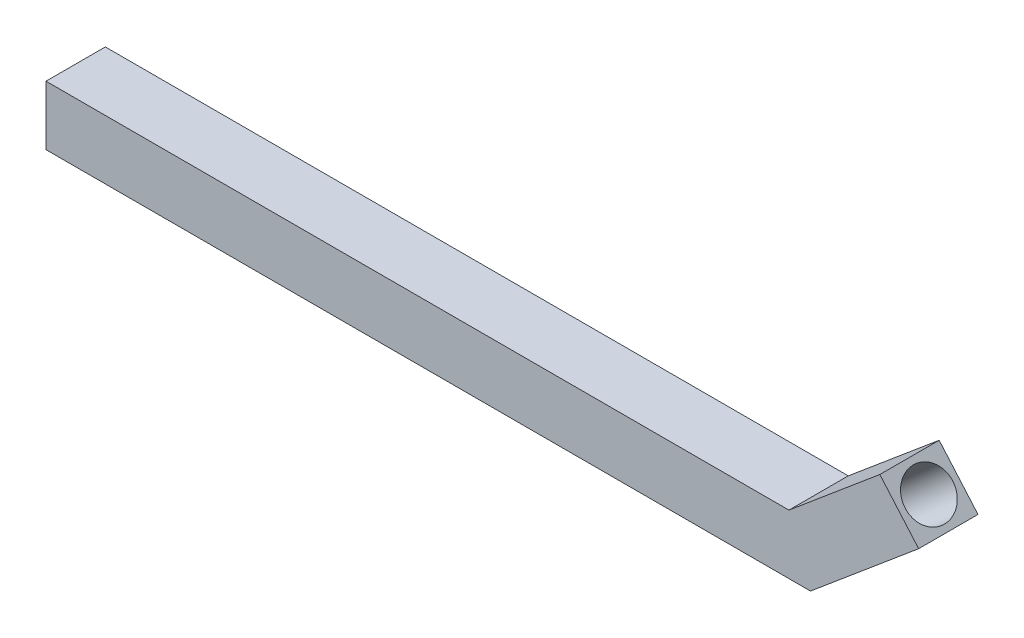
SolidWorks part; units mm, degrees
ref_plane "Front Plane" through (0, 0, 0) normal (0, 0, 1) x (1, 0, 0)
ref_plane "Top Plane" through (0, 0, 0) normal (0, 1, 0) x (1, 0, 0)
ref_plane "Right Plane" through (0, 0, 0) normal (1, 0, 0) x (0, 0, -1)
sketch "Sketch1" plane through (0, 0, 0) normal (0, 0, 1) x (1, 0, 0)
  line L0 (-13.3, 0) -> (0, 0)
  line L1 (0, 0) -> (3.8302, 3.2139)
  line L2 (-13.3, 0) -> (-13.3, -2.5)
  line L3 (-13.3, -2.5) -> (0.9095, -2.5)
  line L4 (0.9095, -2.5) -> (5.466, 1.3234)
  line L5 (5.466, 1.3234) -> (3.8302, 3.2139)
  dimension "D1" = 13.3
  dimension "D2" = 5
  dimension "D3" = 140
  dimension "D4" = 2.5
  dimension "D5" = 2.5
extrude "Boss-Extrude1" add sketch "Sketch1" along normal blind 2.5
sketch "Sketch2" plane through (3.7807, 3.2711, 0) normal (0.7562, 0.6543, 0) x (0, 0, -1)
  line L0 (-2.5, -1.3256) -> (0, -1.3256) construction
  line L1 (-2.5, -2.5756) -> (-2.5, -0.0756) construction
  line L2 (0, -2.5756) -> (0, -0.0756) construction
  line L3 (-1.25, -0.0756) -> (-1.25, -2.5756) construction
  line L4 (-2.5, -0.0756) -> (0, -0.0756) construction
  line L5 (-2.5, -2.5756) -> (0, -2.5756) construction
  circle A0 centre (-1.25, -1.3256) radius 1
  dimension "D1" = 2
extrude "Cut-Extrude1" cut sketch "Sketch2" against normal blind 5
sketch "Sketch3" plane through (-13.3, 0, 0) normal (-1, 0, 0) x (0, 0, 1)
  line L0 (1.25, 0) -> (1.25, -2.5) construction
  line L1 (2.5, 0) -> (0, 0) construction
  line L2 (2.5, -2.5) -> (0, -2.5) construction
  line L3 (0, -1.25) -> (2.5, -1.25) construction
  line L4 (0, 0) -> (0, -2.5) construction
  line L5 (2.5, 0) -> (2.5, -2.5) construction
  circle A0 centre (1.25, -1.25) radius 1
  dimension "D1" = 2
extrude "Cut-Extrude2" cut sketch "Sketch3" against normal blind 5
sketch "Sketch4" plane through (-13.3, 0, 0) normal (-1, 0, 0) x (0, 0, 1)
  line L0 (1.25, 0) -> (1.25, -2.5) construction
  line L1 (2.5, 0) -> (0, 0) construction
  line L2 (2.5, -2.5) -> (0, -2.5) construction
  line L3 (0, -1.25) -> (2.5, -1.25) construction
  line L4 (0, 0) -> (0, -2.5) construction
  line L5 (2.5, 0) -> (2.5, -2.5) construction
  circle A0 centre (1.25, -1.25) radius 1
extrude "Boss-Extrude2" add sketch "Sketch4" against normal blind 5
sketch "Sketch6" plane through (-13.3, 0, 0) normal (-1, 0, 0) x (0, 0, 1)
  line L0 (1.25, 0) -> (1.25, -2.5) construction
  line L1 (2.5, 0) -> (0, 0) construction
  line L2 (2.5, -2.5) -> (0, -2.5) construction
  line L3 (0, -1.25) -> (2.5, -1.25) construction
  line L4 (0, 0) -> (0, -2.5) construction
  line L5 (2.5, 0) -> (2.5, -2.5) construction
  line L7 (0, 0) -> (2.5, 0)
  line L8 (0, 0) -> (0, -2.5)
  line L9 (0, -2.5) -> (2.5, -2.5)
  line L10 (2.5, 0) -> (2.5, -2.5)
  line L11 (0, 0) -> (2.5, -2.5) construction
  line L12 (0, -2.5) -> (2.5, 0) construction
  point P12 (1.25, -1.25)
extrude "Boss-Extrude3" add sketch "Sketch6" along normal blind 25
sketch "Sketch7" plane through (-38.3, 0, 0) normal (-1, 0, 0) x (0, 0, 1)
  line L0 (1.25, 0) -> (1.25, -2.5) construction
  line L1 (2.5, 0) -> (0, 0) construction
  line L2 (0, -2.5) -> (2.5, -2.5) construction
  line L3 (0, -1.25) -> (2.5, -1.25) construction
  line L4 (0, 0) -> (0, -2.5) construction
  line L5 (2.5, -2.5) -> (2.5, 0) construction
  circle A0 centre (1.25, -1.25) radius 1
  dimension "D1" = 2
extrude "Cut-Extrude3" cut sketch "Sketch7" against normal blind 5
sketch "Sketch8" plane through (0, 0, 0) normal (0, 0, -1) x (-1, 0, 0)
  line L0 (38.3, 0) -> (30.3, 0)
  line L1 (0, 0) -> (38.3, 0) construction
  line L2 (30.3, 0) -> (30.3, -2.5)
  line L3 (38.3, -2.5) -> (-0.9095, -2.5) construction
  line L4 (30.3, -2.5) -> (38.3, -2.5)
  line L5 (38.3, -2.5) -> (38.3, 0)
  dimension "D1" = 8
extrude "Cut-Extrude4" cut sketch "Sketch8" against normal blind 10
sketch "Sketch9" plane through (-30.3, 0, 0) normal (-1, 0, 0) x (0, 0, 1)
  line L0 (1.25, 0) -> (1.25, -2.5) construction
  line L1 (2.5, 0) -> (0, 0) construction
  line L2 (2.5, -2.5) -> (0, -2.5) construction
  line L3 (0, -1.25) -> (2.5, -1.25) construction
  line L4 (0, 0) -> (0, -2.5) construction
  line L5 (2.5, -2.5) -> (2.5, 0) construction
  circle A2 centre (1.25, -1.25) radius 1
  dimension "D1" = 2
extrude "Cut-Extrude5" cut sketch "Sketch9" against normal blind 5
sketch "Sketch10" plane through (-30.3, 0, 0) normal (-1, 0, 0) x (0, 0, 1)
  circle A0 centre (1.25, -1.25) radius 1
extrude "Boss-Extrude4" add sketch "Sketch10" against normal blind 5
sketch "Sketch11" plane through (-30.3, 0, 0) normal (-1, 0, 0) x (0, 0, 1)
  line L0 (0, -1.25) -> (2.5, -1.25) construction
  line L1 (0, 0) -> (0, -2.5) construction
  line L2 (2.5, -2.5) -> (2.5, 0) construction
  line L3 (1.25, 0) -> (1.25, -2.5) construction
  line L4 (2.5, 0) -> (0, 0) construction
  line L5 (2.5, -2.5) -> (0, -2.5) construction
  line L7 (0, 0) -> (2.5, 0)
  line L8 (0, 0) -> (0, -2.5)
  line L9 (0, -2.5) -> (2.5, -2.5)
  line L10 (2.5, 0) -> (2.5, -2.5)
  line L11 (0, 0) -> (2.5, -2.5) construction
  line L12 (0, -2.5) -> (2.5, 0) construction
  point P12 (1.25, -1.25)
extrude "Boss-Extrude5" add sketch "Sketch11" along normal blind 1
sketch "Sketch12" plane through (-31.3, 0, 0) normal (-1, 0, 0) x (0, 0, 1)
  line L0 (0, -1.25) -> (2.5, -1.25) construction
  line L1 (0, 0) -> (0, -2.5) construction
  line L2 (2.5, -2.5) -> (2.5, 0) construction
  line L3 (1.25, 0) -> (1.25, -2.5) construction
  line L4 (2.5, 0) -> (0, 0) construction
  line L5 (0, -2.5) -> (2.5, -2.5) construction
  line L11 (0, 0) -> (2.5, 0)
  line L12 (0, 0) -> (0, -2.5)
  line L13 (0, -2.5) -> (2.5, -2.5)
  line L14 (2.5, 0) -> (2.5, -2.5)
  line L15 (0, 0) -> (2.5, -2.5) construction
  line L16 (0, -2.5) -> (2.5, 0) construction
  point P12 (1.25, -1.25)
extrude "Boss-Extrude6" add sketch "Sketch12" along normal blind 1
sketch "Sketch13" plane through (-32.3, 0, 0) normal (-1, 0, 0) x (0, 0, 1)
  line L5 (0, 0) -> (2.5, 0)
  line L6 (0, 0) -> (0, -2.5)
  line L7 (0, -2.5) -> (2.5, -2.5)
  line L8 (2.5, 0) -> (2.5, -2.5)
extrude "Cut-Extrude6" cut sketch "Sketch13" against normal blind 1
sketch "Sketch14" plane through (-31.3, 0, 0) normal (-1, 0, 0) x (0, 0, 1)
  line L3 (0, -1.25) -> (2.5, -1.25)
  line L4 (0, 0) -> (0, -2.5) construction
  line L5 (2.5, -2.5) -> (2.5, 0) construction
  circle A0 centre (1.25, -1.25) radius 1
  dimension "D1" = 2
extrude "Cut-Extrude7" cut sketch "Sketch14" against normal blind 5 contours L3 A0 | L3 A0
